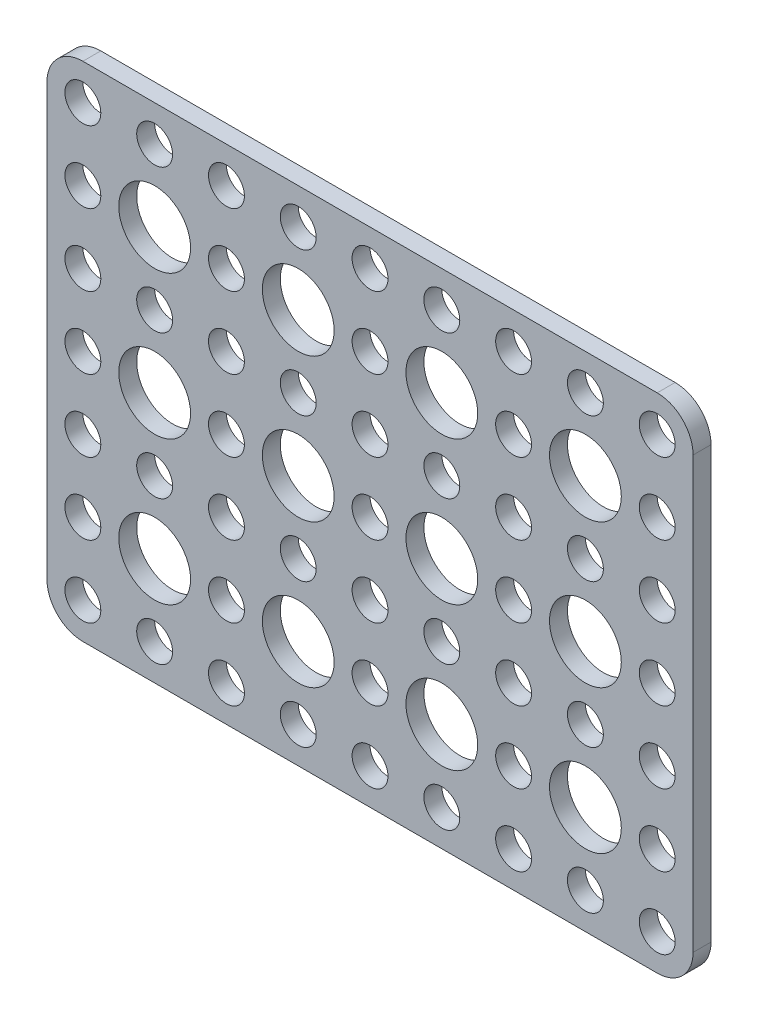
SolidWorks part; units mm, degrees
material "6063-T1"
ref_plane "Front Plane" through (0, 0, 0) normal (0, 0, 1) x (1, 0, 0)
ref_plane "Top Plane" through (0, 0, 0) normal (0, 1, 0) x (1, 0, 0)
ref_plane "Right Plane" through (0, 0, 0) normal (1, 0, 0) x (0, 0, -1)
sketch "Sketch1" plane through (0, 0, 0) normal (0, 0, 1) x (1, 0, 0)
  line L1 (-36, 28) -> (36, 28)
  line L2 (-36, 28) -> (-36, -28)
  line L3 (-36, -28) -> (36, -28)
  line L4 (36, 28) -> (36, -28)
  line L5 (-36, 28) -> (36, -28) construction
  line L6 (-36, -28) -> (36, 28) construction
  point P0 (0, 0)
  dimension "D1" = 72
  dimension "D2" = 56
extrude "Boss-Extrude1" add sketch "Sketch1" along normal blind 2
sketch "Sketch2" plane through (0, 0, 2) normal (0, 0, 1) x (1, 0, 0)
  line L0 (36, 28) -> (-36, 28) construction
  line L1 (-36, 28) -> (-36, -28) construction
  circle A0 centre (-32, 24) radius 2
  dimension "D1" = 4
  dimension "D2" = 4
  dimension "D3" = 4
extrude "Cut-Extrude1" cut sketch "Sketch2" against normal blind 3
pattern_linear "LPattern1" count 9 spacing 8 along (1, 0, 0) count 7 spacing 8 along (0, -1, 0) of "Cut-Extrude1"
sketch "Sketch4" plane through (0, 0, 2) normal (0, 0, 1) x (1, 0, 0)
  circle A0 centre (-24, 16) radius 4
  dimension "D1" = 8
extrude "Cut-Extrude2" cut sketch "Sketch4" against normal blind 3
pattern_linear "LPattern2" count 4 spacing 16 along (1, 0, 0) count 3 spacing 16 along (0, -1, 0) of "Cut-Extrude2"
fillet "Fillet1" radius 4 4 edges at (-36, -28, 1) (36, -28, 1) (36, 28, 1) (-36, 28, 1)
